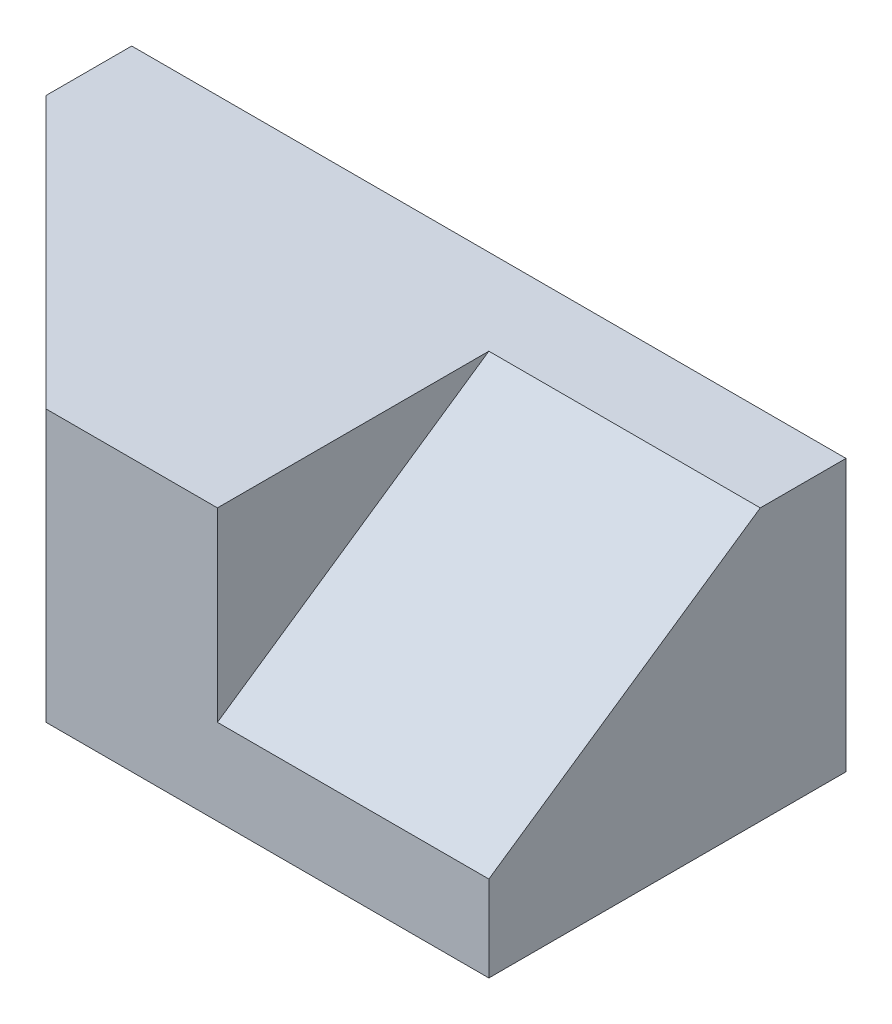
SolidWorks part; units mm, degrees
ref_plane "Front Plane" through (0, 0, 0) normal (0, 0, 1) x (1, 0, 0)
ref_plane "Top Plane" through (0, 0, 0) normal (0, 1, 0) x (1, 0, 0)
ref_plane "Right Plane" through (0, 0, 0) normal (1, 0, 0) x (0, 0, -1)
sketch "Sketch1" plane through (0, 0, 0) normal (0, 1, 0) x (1, 0, 0)
  line L7 (-100, 50) -> (-100, 38)
  line L8 (-100, 38) -> (-62, 0)
  line L9 (-62, 0) -> (0, 0)
  line L10 (0, 0) -> (0, 50)
  line L11 (0, 50) -> (-100, 50)
  point P3 (0, 0)
  dimension "D1" = 12
  dimension "D2" = 62
  dimension "D3" = 50
  dimension "D4" = 100
extrude "Boss-Extrude1" add sketch "Sketch1" along normal blind 38
sketch "Sketch2" plane through (0, 0, 0) normal (1, 0, 0) x (0, 0, -1)
  line L0 (38, 38) -> (0, 12)
  line L1 (0, 38) -> (50, 38) construction
  line L2 (0, 38) -> (0, 0) construction
  dimension "D1" = 12
  dimension "D2" = 12
extrude "Cut-Extrude8" cut sketch "Sketch2" against normal blind 38 and the other way through all flip side to cut
